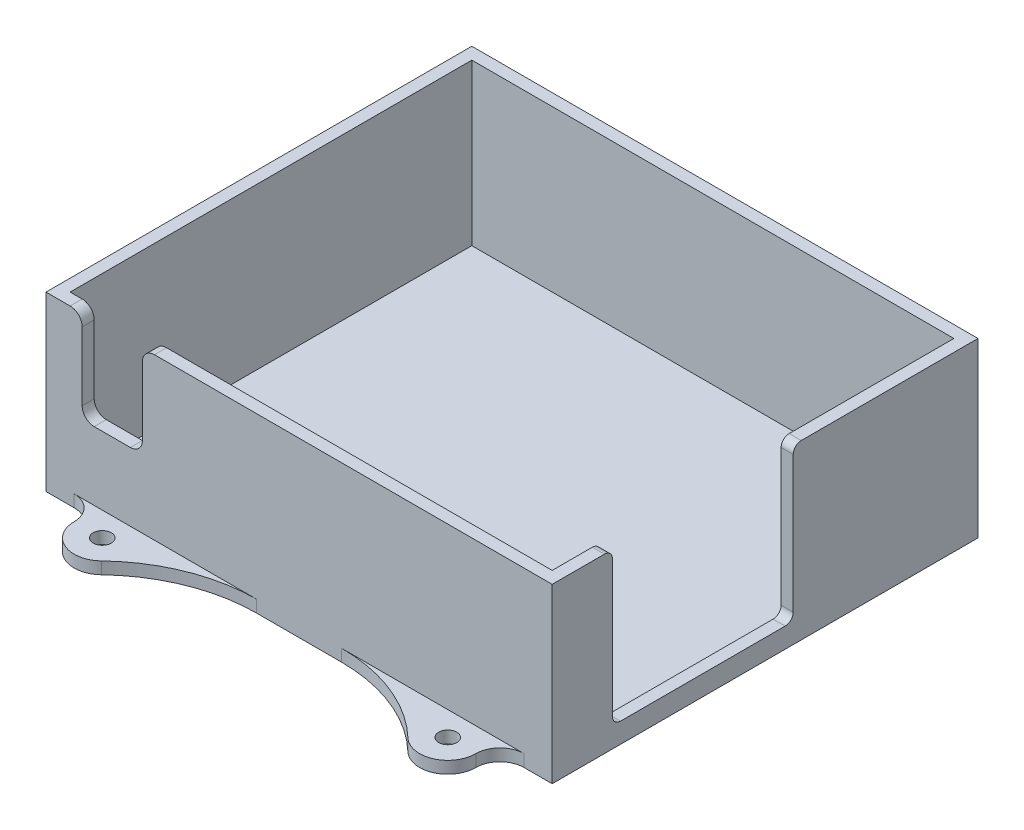
SolidWorks part; units mm, degrees
ref_plane "Front Plane" through (0, 0, 0) normal (0, 0, 1) x (1, 0, 0)
ref_plane "Top Plane" through (0, 0, 0) normal (0, 1, 0) x (1, 0, 0)
ref_plane "Right Plane" through (0, 0, 0) normal (1, 0, 0) x (0, 0, -1)
sketch "Sketch1" plane through (0, 0, 0) normal (0, 1, 0) x (1, 0, 0)
  line L0 (-63, -53) -> (-63, 53)
  line L1 (-60, -50) -> (60, -50)
  line L2 (-60, -50) -> (-60, 50)
  line L3 (-60, 50) -> (60, 50)
  line L4 (60, -50) -> (60, 50)
  line L5 (-60, -50) -> (60, 50) construction
  line L6 (-60, 50) -> (60, -50) construction
  line L7 (-63, 53) -> (63, 53)
  line L8 (63, -53) -> (63, 53)
  line L9 (-63, -53) -> (63, -53)
  point P0 (0, 0)
  dimension "D1" = 100
  dimension "D2" = 120
  dimension "D3" = 3
extrude "Boss-Extrude1" add sketch "Sketch1" along normal blind 40 contours L0 L9 L8 L7 L4 L1 L2 L3
sketch "Sketch2" plane through (0, 0, 0) normal (0, -1, 0) x (1, 0, 0)
  line L0 (43, 59) -> (43, -59) construction
  line L1 (56, 53) -> (63, 53)
  line L2 (-63, 53) -> (-63, -53)
  line L3 (-63, -53) -> (-56, -53)
  line L4 (63, 53) -> (63, -53)
  line L5 (-63, 53) -> (63, -53) construction
  line L6 (-63, -53) -> (63, 53) construction
  line L7 (10.55, 53) -> (-10.55, 53)
  line L8 (0, 0) -> (10, 0) construction
  line L9 (0, 0) -> (0, 10) construction
  line L10 (56, -53) -> (63, -53)
  line L11 (-56, 53) -> (-63, 53)
  line L12 (-10.55, -53) -> (10.55, -53)
  circle A0 centre (43, 59) radius 2.25
  arc A2 (50, 59) -> (38.167, 64.0638) centre (43, 59) ccw
  arc A3 (56, 53) -> (50, 59) centre (56, 59) cw
  arc A4 (10.55, 53) -> (38.167, 64.0638) centre (10.55, 93) ccw
  arc A5 (10.55, -53) -> (38.167, -64.0638) centre (10.55, -93) cw
  arc A6 (50, -59) -> (38.167, -64.0638) centre (43, -59) cw
  arc A7 (56, -53) -> (50, -59) centre (56, -59) ccw
  circle A8 centre (43, -59) radius 2.25
  circle A9 centre (-43, -59) radius 2.25
  arc A10 (-10.55, -53) -> (-38.167, -64.0638) centre (-10.55, -93) ccw
  arc A11 (-50, -59) -> (-38.167, -64.0638) centre (-43, -59) ccw
  arc A12 (-56, -53) -> (-50, -59) centre (-56, -59) cw
  circle A13 centre (-43, 59) radius 2.25
  arc A14 (-10.55, 53) -> (-38.167, 64.0638) centre (-10.55, 93) cw
  arc A15 (-50, 59) -> (-38.167, 64.0638) centre (-43, 59) cw
  arc A16 (-56, 53) -> (-50, 59) centre (-56, 59) ccw
  point P0 (0, 0)
  point P18 (39.3944, 53)
  dimension "D4" = 7
  dimension "D5" = 6
  dimension "D6" = 40
  dimension "D1" = 20
  dimension "D2" = 6
  dimension "D7" = 10
  dimension "D8" = 10
extrude "Boss-Extrude2" add sketch "Sketch2" along normal blind 3
sketch "Sketch3" plane through (0, 0, 53) normal (0, 0, 1) x (1, 0, 0)
  line L0 (-63, 40) -> (63, 40) construction
  line L1 (-54, 40) -> (-39, 40)
  line L2 (-54, 40) -> (-54, 17)
  line L3 (-54, 17) -> (-39, 17)
  line L4 (-39, 40) -> (-39, 17)
  line L5 (10.55, -3) -> (-10.55, -3) construction
  line L6 (-63, 40) -> (-63, -3) construction
  dimension "D1" = 15
  dimension "D2" = 20
  dimension "D3" = 9
extrude "Cut-Extrude1" cut sketch "Sketch3" against normal blind 3
fillet "Fillet1" radius 3 4 edges at (-54, 40, 51.5) (-39, 40, 51.5) (-39, 17, 51.5) (-54, 17, 51.5)
sketch "Sketch4" plane through (63, 0, 0) normal (1, 0, 0) x (0, 0, -1)
  line L0 (-53, 40) -> (53, 40) construction
  line L1 (-38, 40) -> (7, 40)
  line L2 (-38, 40) -> (-38, 2)
  line L3 (-38, 2) -> (7, 2)
  line L4 (7, 40) -> (7, 2)
  line L5 (-53, 40) -> (-53, -3) construction
  line L6 (53, -3) -> (-53, -3) construction
  dimension "D1" = 15
  dimension "D2" = 60
  dimension "D3" = 5
extrude "Cut-Extrude2" cut sketch "Sketch4" against normal blind 3
fillet "Fillet2" radius 2 4 edges at (61.5, 2, 38) (61.5, 2, -7) (61.5, 40, 38) (61.5, 40, -7)
